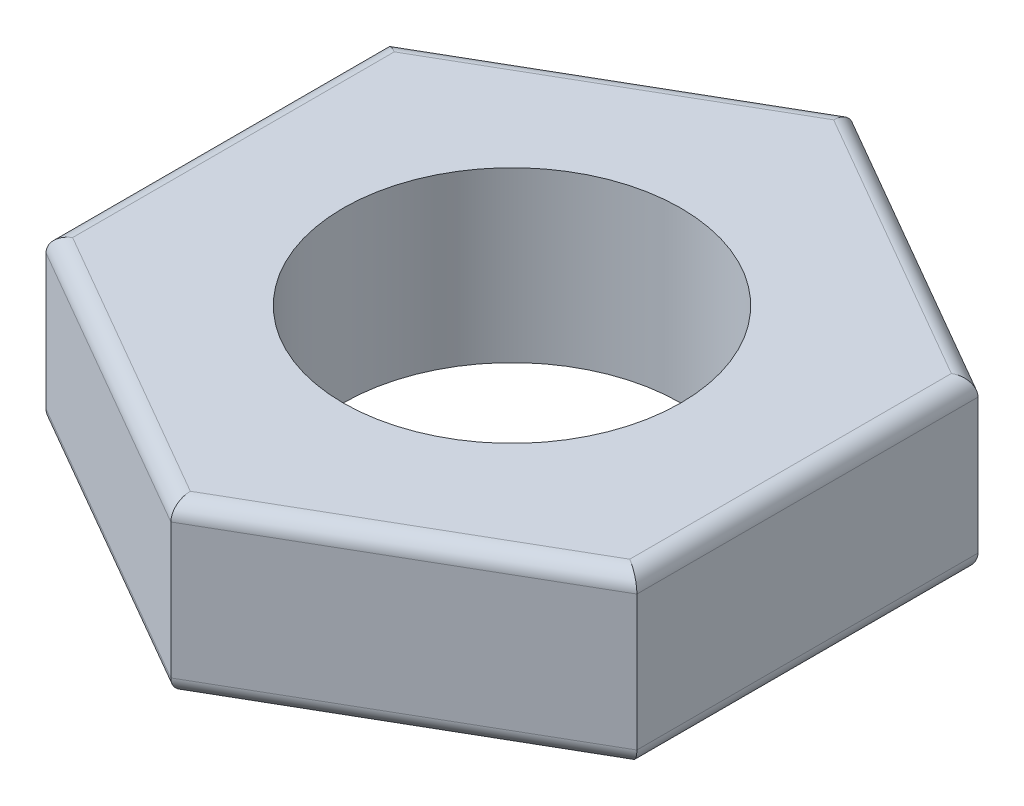
SolidWorks part; units mm, degrees
ref_plane "Front Plane" through (0, 0, 0) normal (0, 0, 1) x (1, 0, 0)
ref_plane "Top Plane" through (0, 0, 0) normal (0, 1, 0) x (1, 0, 0)
ref_plane "Right Plane" through (0, 0, 0) normal (1, 0, 0) x (0, 0, -1)
ref_plane "Plane1" through (0, 2, 0) normal (0, 1, 0) x (1, 0, 0)
sketch "Sketch1" plane through (0, 2, 0) normal (0, 1, 0) x (1, 0, 0)
  line L0 (0, 4.0415) -> (-3.5, 2.0207)
  line L1 (-3.5, 2.0207) -> (-3.5, -2.0207)
  line L2 (-3.5, -2.0207) -> (0, -4.0415)
  line L3 (0, -4.0415) -> (3.5, -2.0207)
  line L4 (3.5, -2.0207) -> (3.5, 2.0207)
  line L5 (3.5, 2.0207) -> (0, 4.0415)
extrude "Boss-Extrude1" add sketch "Sketch1" against normal blind 2
hole_wizard "Ø4.0 (4) Diameter Hole1" positions "Sketch3" profile "Sketch2" hole size "Ø4.0" standard "ANSI Metric"
sketch "Sketch3" plane through (0, 0, 0) normal (0, -1, 0) x (-1, 0, 0)
  point P0 (0, 0)
sketch "Sketch2" plane through (0, 0, 0) normal (1, 0, 0) x (0, 0, -1)
  line L0 (0, 0) -> (0, 2)
  line L1 (0, 2) -> (2, 2)
  line L2 (2, 2) -> (2, 0)
  line L5 (2, 0) -> (0, 0)
  line L11 (0, -6.35) -> (0, 107.95) construction
  dimension "Thru Hole Dia." = 4
  dimension "Thru Hole Depth" = 2
fillet "Fillet1" radius 0.2 12 edges at (1.75, 2, 3.0311) (-1.75, 2, 3.0311) (3.5, 2, 0) (-3.5, 2, 0) (1.75, 2, -3.0311) (-1.75, 2, -3.0311) (1.75, 0, 3.0311) (-1.75, 0, 3.0311) (3.5, 0, 0) (-3.5, 0, 0) (1.75, 0, -3.0311) (-1.75, 0, -3.0311)
